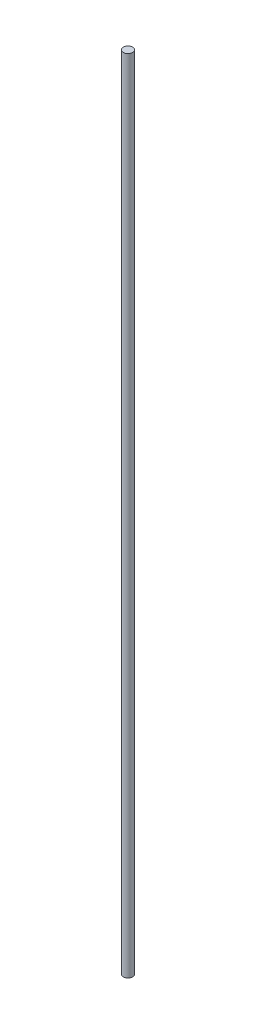
SolidWorks part; units mm, degrees
material "AISI 1020"
ref_plane "Front Plane" through (0, 0, 0) normal (0, 0, 1) x (1, 0, 0)
ref_plane "Top Plane" through (0, 0, 0) normal (0, 1, 0) x (1, 0, 0)
ref_plane "Right Plane" through (0, 0, 0) normal (1, 0, 0) x (0, 0, -1)
sketch "Sketch1" plane through (0, 0, 0) normal (0, 1, 0) x (1, 0, 0)
  circle A0 centre (0, 0) radius 2.5
  dimension "D1" = 5
extrude "Boss-Extrude1" add sketch "Sketch1" along normal mid plane 430
cosmetic thread "Cosmetic Thread1" parameters "D2"=4
